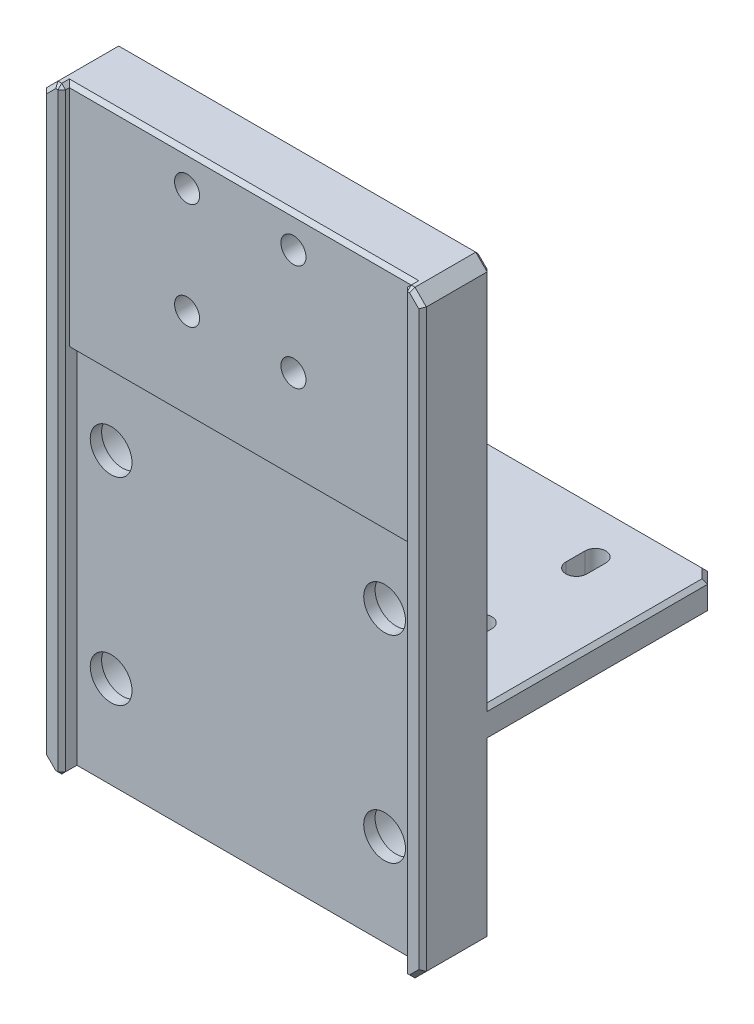
SolidWorks part; units mm, degrees
material "Q235-A"
ref_plane "前视基准面" through (0, 0, 0) normal (0, 0, 1) x (1, 0, 0)
ref_plane "上视基准面" through (0, 0, 0) normal (0, 1, 0) x (1, 0, 0)
ref_plane "右视基准面" through (0, 0, 0) normal (1, 0, 0) x (0, 0, -1)
sketch "草图1" plane through (0, 0, 0) normal (0, 0, 1) x (1, 0, 0)
  line L1 (-50, 78.75) -> (50, 78.75)
  line L2 (-50, 78.75) -> (-50, -78.75)
  line L3 (-50, -78.75) -> (50, -78.75)
  line L4 (50, 78.75) -> (50, -78.75)
  line L5 (-50, 78.75) -> (50, -78.75) construction
  line L6 (-50, -78.75) -> (50, 78.75) construction
  point P0 (0, 0)
  dimension "D1" = 157.5
  dimension "D2" = 100
extrude "凸台-拉伸1" add sketch "草图1" along normal blind 18
sketch "草图2" plane through (0, 0, 18) normal (0, 0, 1) x (1, 0, 0)
  line L1 (-45, -110) -> (45, -110)
  line L2 (-45, -110) -> (-45, 110)
  line L3 (-45, 110) -> (45, 110)
  line L4 (45, -110) -> (45, 110)
  line L5 (-45, -110) -> (45, 110) construction
  line L6 (-45, 110) -> (45, -110) construction
  point P0 (0, 0)
  dimension "D1" = 90
  dimension "D2" = 220
extrude "切除-拉伸1" cut sketch "草图2" against normal blind 2
sketch "草图3" plane through (0, 0, 16) normal (0, 0, 1) x (1, 0, 0)
  line L0 (45, -78.75) -> (-45, -78.75) construction
  line L1 (-45, -176.25) -> (45, -176.25)
  line L2 (-45, -176.25) -> (-45, 18.75)
  line L3 (-45, 18.75) -> (45, 18.75)
  line L4 (45, -176.25) -> (45, 18.75)
  line L5 (-45, -176.25) -> (45, 18.75) construction
  line L6 (-45, 18.75) -> (45, -176.25) construction
  line L8 (45, -78.75) -> (45, 78.75) construction
  line L9 (-45, 78.75) -> (45, 78.75) construction
  point P0 (0, -78.75)
  dimension "D1" = 60
extrude "切除-拉伸2" cut sketch "草图3" against normal blind 2
sketch "草图4" plane through (-50, 0, 0) normal (-1, 0, 0) x (0, 0, 1)
  line L0 (0, 78.75) -> (0, -78.75) construction
  line L2 (0, -31.5) -> (-60, -31.5)
  line L3 (0, -31.5) -> (0, -23.5)
  line L4 (0, -23.5) -> (-60, -23.5)
  line L5 (-60, -31.5) -> (-60, -23.5)
  line L6 (18, -78.75) -> (0, -78.75) construction
  dimension "D1" = 60
  dimension "D2" = 8
  dimension "D3" = 47.25
extrude "凸台-拉伸2" add sketch "草图4" against normal up to surface (100 mm away) up to face at (50, 0, 9)
sketch "草图5" plane through (0, 0, 0) normal (1, 0, 0) x (0, 0, -1)
  line L0 (0, -31.5) -> (0, -78.75) construction
  line L1 (60, -31.5) -> (0, -31.5) construction
  line L2 (0, -31.5) -> (0, -78.75)
  line L3 (60, -31.5) -> (0, -31.5)
  line L4 (60, -31.5) -> (60, -39.5)
  line L5 (60, -39.5) -> (8, -78.75)
  line L6 (8, -78.75) -> (0, -78.75)
  dimension "D1" = 8
extrude "凸台-拉伸3" add sketch "草图5" along normal mid plane 12
hole_wizard "打孔尺寸(%根据)内六角圆柱头螺钉的类型0" positions "草图6" profile "草图7" counterbore size "M10" standard "GB" end condition through all
sketch "草图6" plane through (0, 0, 0) normal (0, 0, -1) x (-1, 0, 0)
  point P0 (-36, -1.5)
  point P3 (36, -1.5)
  point P6 (36, -53.5)
  point P9 (-36, -53.5)
sketch "草图7" plane through (36, -1.5, 0) normal (1, 0, 0) x (0, 1, 0)
  line L0 (0, 0) -> (0, 18)
  line L1 (0, 18) -> (5.5, 18)
  line L3 (5.5, 18) -> (5.5, 11)
  line L4 (5.5, 11) -> (9, 11)
  line L5 (9, 11) -> (9, 0)
  line L7 (9, 0) -> (0, 0)
  line L11 (0, -6.35) -> (0, 107.95) construction
  dimension "通孔孔直径" = 11
  dimension "通孔孔深度" = 18
  dimension "柱形沉头孔直径" = 18
  dimension "柱形沉头孔深度" = 11
hole_wizard "打孔尺寸(%根据)内六角圆柱头螺钉的类型1" positions "草图8" profile "草图10" counterbore size "M6" standard "GB" end condition through all
sketch "草图8" plane through (0, 0, 0) normal (0, 0, -1) x (-1, 0, 0)
  point P0 (-14, 70.25)
  point P2 (-14, 42.25)
  point P4 (14, 70.25)
  point P6 (14, 42.25)
sketch "草图10" plane through (14, 70.25, 0) normal (1, 0, 0) x (0, 1, 0)
  line L0 (0, 0) -> (0, 18)
  line L1 (0, 18) -> (3.3, 18)
  line L3 (3.3, 18) -> (3.3, 6.8)
  line L4 (3.3, 6.8) -> (5.5, 6.8)
  line L5 (5.5, 6.8) -> (5.5, 0)
  line L7 (5.5, 0) -> (0, 0)
  line L11 (0, -6.35) -> (0, 107.95) construction
  dimension "通孔孔直径" = 6.6
  dimension "通孔孔深度" = 18
  dimension "柱形沉头孔直径" = 11
  dimension "柱形沉头孔深度" = 6.8
fillet "圆角1" radius 10 2 edges at (0, -78.75, -8) (0, -39.5, -60)
sketch "草图12" plane through (0, -31.5, 0) normal (0, -1, 0) x (1, 0, 0)
  line L0 (0, -60) -> (0, 0) construction
  line L1 (6, -60) -> (-6, -60) construction
  line L2 (30, -30) -> (-30, -30) construction
  line L3 (30, -45) -> (30, -15) construction
  line L4 (-30, -45) -> (-30, -15) construction
  line L5 (30, -42.5) -> (30, -47.5) construction
  line L6 (32.75, -42.5) -> (32.75, -47.5)
  line L7 (27.25, -42.5) -> (27.25, -47.5)
  line L8 (30, -12.5) -> (30, -17.5) construction
  line L9 (32.75, -12.5) -> (32.75, -17.5)
  line L10 (27.25, -12.5) -> (27.25, -17.5)
  line L11 (-30, -47.5) -> (-30, -42.5) construction
  line L12 (-32.75, -47.5) -> (-32.75, -42.5)
  line L13 (-27.25, -47.5) -> (-27.25, -42.5)
  line L14 (-30, -12.5) -> (-30, -17.5) construction
  line L15 (-27.25, -12.5) -> (-27.25, -17.5)
  line L16 (-32.75, -12.5) -> (-32.75, -17.5)
  arc A4 (32.75, -42.5) -> (27.25, -42.5) centre (30, -42.5) ccw
  arc A5 (27.25, -47.5) -> (32.75, -47.5) centre (30, -47.5) ccw
  arc A6 (32.75, -12.5) -> (27.25, -12.5) centre (30, -12.5) ccw
  arc A7 (27.25, -17.5) -> (32.75, -17.5) centre (30, -17.5) ccw
  arc A8 (-32.75, -47.5) -> (-27.25, -47.5) centre (-30, -47.5) ccw
  arc A9 (-27.25, -42.5) -> (-32.75, -42.5) centre (-30, -42.5) ccw
  arc A10 (-27.25, -12.5) -> (-32.75, -12.5) centre (-30, -12.5) ccw
  arc A11 (-32.75, -17.5) -> (-27.25, -17.5) centre (-30, -17.5) ccw
  point P8 (0, -30)
  point P11 (30, -30)
  point P13 (-30, -30)
  point P16 (30, -45)
  point P22 (30, -15)
  point P30 (-30, -45)
  point P36 (-30, -15)
  dimension "D3" = 5.5
  dimension "D1" = 60
  dimension "D2" = 30
  dimension "D4" = 5
extrude "切除-拉伸3" cut sketch "草图12" against normal through all
chamfer "倒角1" distance 3 angle 45 6 edges at (-50, -27.5, -60) (50, -27.5, -60) (-50, -78.75, 9) (50, -78.75, 9) (50, 78.75, 9) (-50, 78.75, 9)
chamfer "倒角2" distance 1 angle 45 50 edges at (-45, 78.75, 17) (0, 78.75, 16) (45, 78.75, 17) (-48.5, 77.25, 18) (-46, 78.75, 18) (-50, 0, 18) (-45, 0, 18) (-48.5, -77.25, 18) (-46, -78.75, 18) (-45, -78.75, 16) (0, -78.75, 14) (45, -78.75, 16) (46, -78.75, 18) (48.5, -77.25, 18) (45, 0, 18) (46, 78.75, 18) (48.5, 77.25, 18) (50, 0, 18) (26.5, -78.75, 0) (48.5, -77.25, 0) (50, -53.625, 0) (50, -31.5, -28.5) (48.5, -31.5, -58.5) (26.5, -31.5, -60) (-26.5, -78.75, 0) (-48.5, -77.25, 0) (-50, -53.625, 0) (-26.5, -31.5, -60) (-48.5, -31.5, -58.5) (-50, -31.5, -28.5) (48.5, 77.25, 0) (0, 78.75, 0) (-48.5, 77.25, 0) (-50, 26.125, 0) (-50, -23.5, -28.5) (-48.5, -23.5, -58.5) (0, -23.5, -60) (48.5, -23.5, -58.5) (50, -23.5, -28.5) (50, 26.125, 0) (6, -78.75, -2.3248) (6, -33.0096, -60) (6, -78.232, -7.8264) (6, -38.9776, -58.9511) (6, -59.6161, -33.3493) (-6, -78.75, -2.3248) (-6, -33.0096, -60) (-6, -78.232, -7.8264) (-6, -38.9776, -58.9511) (-6, -59.6161, -33.3493)
